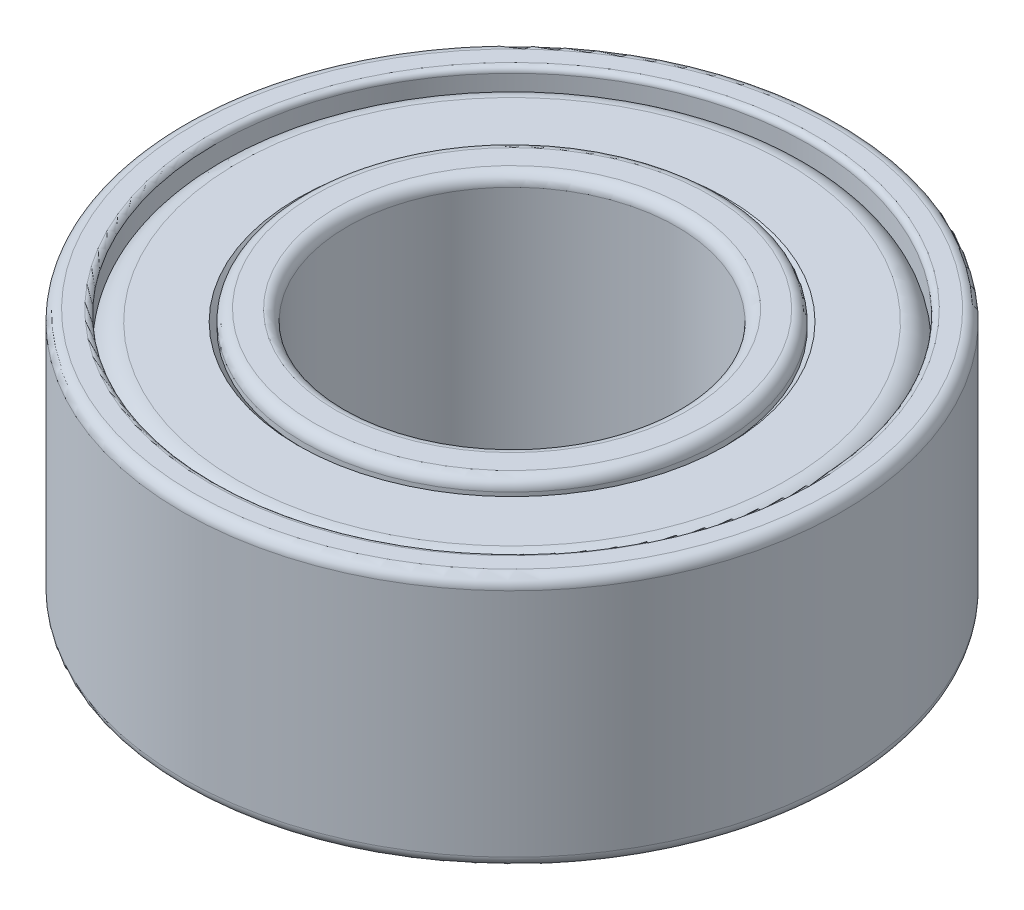
SolidWorks part; units mm, degrees
material "1060 Alloy"
ref_plane "Front Plane" through (0, 0, 0) normal (0, 0, 1) x (1, 0, 0)
ref_plane "Top Plane" through (0, 0, 0) normal (0, 1, 0) x (1, 0, 0)
ref_plane "Right Plane" through (0, 0, 0) normal (1, 0, 0) x (0, 0, -1)
sketch "Sketch2" plane through (0, 0, 0) normal (0, 1, 0) x (1, 0, 0)
  circle A0 centre (0, 0) radius 1.5
  circle A1 centre (0, 0) radius 1.9
  dimension "D1" = 3
  dimension "D2" = 0.4
extrude "Boss-Extrude1" add sketch "Sketch2" along normal mid plane 2.3
sketch "Sketch4" plane through (0, 0, 0) normal (0, 1, 0) x (1, 0, 0)
  circle A0 centre (0, 0) radius 3
  circle A1 centre (0, 0) radius 2.7
  dimension "D1" = 6
  dimension "D2" = 0.3
extrude "Boss-Extrude2" add sketch "Sketch4" along normal mid plane 2.3 separate body
fillet "Fillet1" radius 0.1 4 edges at (0, -1.15, 1.5) (0, -1.15, 1.9) (0, 1.15, 1.5) (0, 1.15, 1.9)
fillet "Fillet2" radius 0.1 2 edges at (0, -1.15, 3) (0, 1.15, 3)
fillet "Fillet3" radius 0.05 2 edges at (0, -1.15, 2.7) (0, 1.15, 2.7)
sketch "Sketch5" plane through (0, 0, 0) normal (0, 1, 0) x (1, 0, 0)
  circle A0 centre (0, 0) radius 2.7
  circle A1 centre (0, 0) radius 2.7 construction
  circle A2 centre (0, 0) radius 1.9
  circle A3 centre (0, 0) radius 1.9 construction
extrude "Boss-Extrude3" add sketch "Sketch5" along normal mid plane 2.1 separate body
fillet "Fillet4" radius 0.2 2 edges at (0, -1.05, 2.7) (0, 1.05, 2.7)
chamfer "Chamfer1" distance 0.05 angle 45 2 edges at (0, -1.05, 1.9) (0, 1.05, 1.9)
